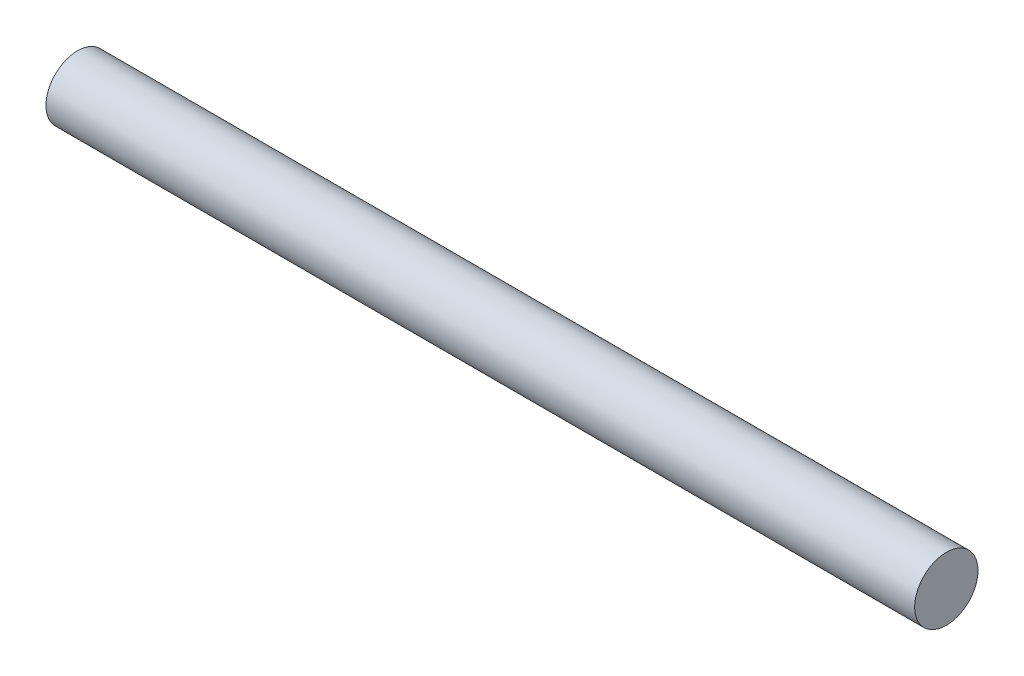
SolidWorks part; units mm, degrees
ref_plane "Front Plane" through (0, 0, 0) normal (1, 0, 0) x (0, 1, 0)
ref_plane "Top Plane" through (0, 0, 0) normal (0, 0, 1) x (0, 1, 0)
ref_plane "Right Plane" through (0, 0, 0) normal (0, 1, 0) x (-1, 0, 0)
sketch "Sketch1" plane through (0, 0, 0) normal (1, 0, 0) x (0, 1, 0)
  circle A0 centre (0, 0) radius 0.875
  dimension "D1" = 1.75
extrude "Boss-Extrude1" add sketch "Sketch1" along normal blind 24 contours A0
